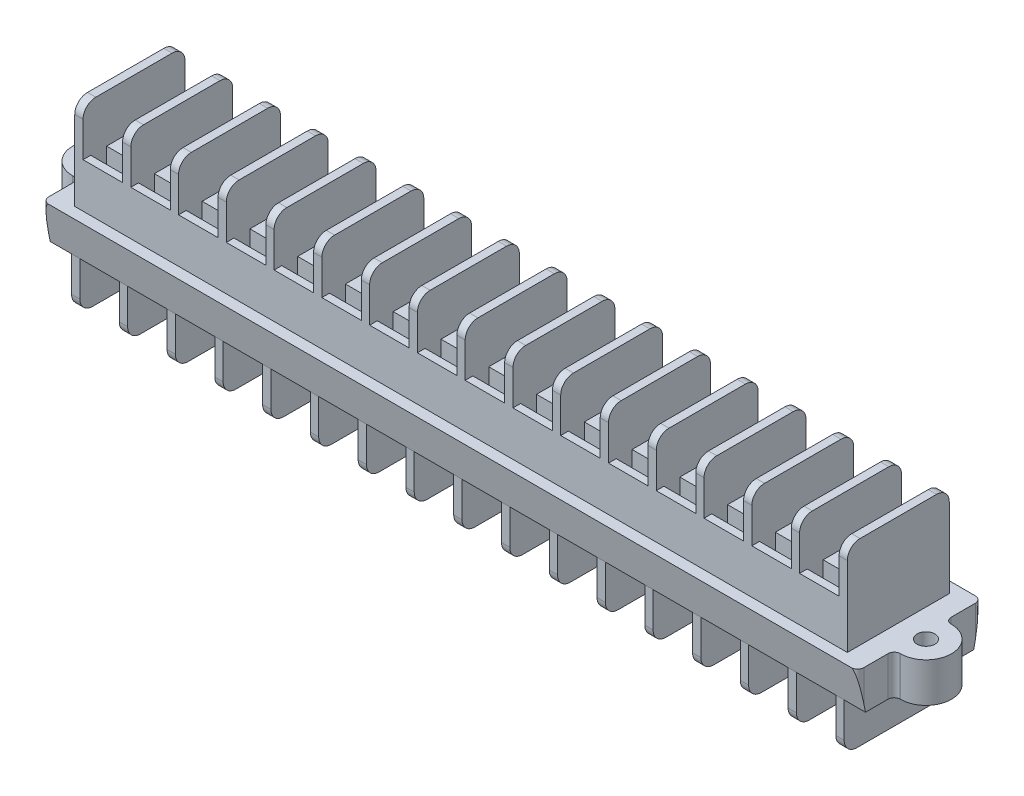
SolidWorks part; units mm, degrees
ref_plane "前视基准面" through (0, 0, 0) normal (0, 0, 1) x (1, 0, 0)
ref_plane "上视基准面" through (0, 0, 0) normal (0, 1, 0) x (1, 0, 0)
ref_plane "右视基准面" through (0, 0, 0) normal (1, 0, 0) x (0, 0, -1)
sketch "草图1" plane through (0, 0, 0) normal (0, 1, 0) x (1, 0, 0)
  line L0 (-82.1935, 0) -> (84.8449, 0) construction
  line L1 (-60.65, 8) -> (60.65, 8)
  line L2 (-60.65, 8) -> (-60.65, -8)
  line L3 (-60.65, -8) -> (60.65, -8)
  line L4 (60.65, 8) -> (60.65, -8)
  line L5 (0, -27.2716) -> (0, 19.3174) construction
  dimension "D1" = 121.3
  dimension "D2" = 16
extrude "拉伸1" add sketch "草图1" along normal blind 14.5
fillet "圆角1" radius 2 2 edges at (0, 14.5, 8) (0, 14.5, -8)
sketch "草图2" plane through (0, 14.5, 0) normal (0, 1, 0) x (-1, 0, 0)
  line L0 (-64.5515, 0) -> (65.0244, 0) construction
  line L1 (-60.65, -8) -> (60.65, -8) construction
  line L2 (-59.35, -8) -> (-53.15, -8)
  line L3 (-59.35, -8) -> (-59.35, 8)
  line L4 (-59.35, 8) -> (-53.15, 8)
  line L5 (-53.15, -8) -> (-53.15, 8)
  line L6 (60.65, 8) -> (-60.65, 8) construction
  line L7 (-60.65, 6) -> (-60.65, -6) construction
  line L8 (-51.85, -8) -> (-45.65, -8)
  line L9 (-51.85, -8) -> (-51.85, 8)
  line L10 (-51.85, 8) -> (-45.65, 8)
  line L11 (-45.65, -8) -> (-45.65, 8)
  line L12 (-44.35, -8) -> (-38.15, -8)
  line L13 (-44.35, -8) -> (-44.35, 8)
  line L14 (-44.35, 8) -> (-38.15, 8)
  line L15 (-38.15, -8) -> (-38.15, 8)
  line L16 (-36.85, -8) -> (-30.65, -8)
  line L17 (-36.85, -8) -> (-36.85, 8)
  line L18 (-36.85, 8) -> (-30.65, 8)
  line L19 (-30.65, -8) -> (-30.65, 8)
  line L20 (-29.35, -8) -> (-23.15, -8)
  line L21 (-29.35, -8) -> (-29.35, 8)
  line L22 (-29.35, 8) -> (-23.15, 8)
  line L23 (-23.15, -8) -> (-23.15, 8)
  line L24 (-21.85, -8) -> (-15.65, -8)
  line L25 (-21.85, -8) -> (-21.85, 8)
  line L26 (-21.85, 8) -> (-15.65, 8)
  line L27 (-15.65, -8) -> (-15.65, 8)
  line L28 (-14.35, -8) -> (-8.15, -8)
  line L29 (-14.35, -8) -> (-14.35, 8)
  line L30 (-14.35, 8) -> (-8.15, 8)
  line L31 (-8.15, -8) -> (-8.15, 8)
  line L32 (-6.85, -8) -> (-0.65, -8)
  line L33 (-6.85, -8) -> (-6.85, 8)
  line L34 (-6.85, 8) -> (-0.65, 8)
  line L35 (-0.65, -8) -> (-0.65, 8)
  line L36 (0.65, -8) -> (6.85, -8)
  line L37 (0.65, -8) -> (0.65, 8)
  line L38 (0.65, 8) -> (6.85, 8)
  line L39 (6.85, -8) -> (6.85, 8)
  line L40 (8.15, -8) -> (14.35, -8)
  line L41 (8.15, -8) -> (8.15, 8)
  line L42 (8.15, 8) -> (14.35, 8)
  line L43 (14.35, -8) -> (14.35, 8)
  line L44 (15.65, -8) -> (21.85, -8)
  line L45 (15.65, -8) -> (15.65, 8)
  line L46 (15.65, 8) -> (21.85, 8)
  line L47 (21.85, -8) -> (21.85, 8)
  line L48 (23.15, -8) -> (29.35, -8)
  line L49 (23.15, -8) -> (23.15, 8)
  line L50 (23.15, 8) -> (29.35, 8)
  line L51 (29.35, -8) -> (29.35, 8)
  line L52 (30.65, -8) -> (36.85, -8)
  line L53 (30.65, -8) -> (30.65, 8)
  line L54 (30.65, 8) -> (36.85, 8)
  line L55 (36.85, -8) -> (36.85, 8)
  line L56 (38.15, -8) -> (44.35, -8)
  line L57 (38.15, -8) -> (38.15, 8)
  line L58 (38.15, 8) -> (44.35, 8)
  line L59 (44.35, -8) -> (44.35, 8)
  line L60 (45.65, -8) -> (51.85, -8)
  line L61 (45.65, -8) -> (45.65, 8)
  line L62 (45.65, 8) -> (51.85, 8)
  line L63 (51.85, -8) -> (51.85, 8)
  line L64 (53.15, -8) -> (59.35, -8)
  line L65 (53.15, -8) -> (53.15, 8)
  line L66 (53.15, 8) -> (59.35, 8)
  line L67 (59.35, -8) -> (59.35, 8)
  dimension "D1" = 1.3
  dimension "D2" = 7.5
extrude "切除-拉伸1" cut sketch "草图2" against normal blind 7.5
sketch "草图3" plane through (0, 0, 0) normal (0, -1, 0) x (1, 0, 0)
  line L0 (63, 9.75) -> (-63, 9.75)
  line L1 (-64, 8.75) -> (-64, 4.95)
  line L2 (-64.95, 4) -> (-65, 4)
  line L3 (76.798, 0) -> (-85.9187, 0) construction
  line L4 (-65, 12.2492) -> (-65, -13.694) construction
  line L5 (-65, -12.2492) -> (-65, 13.694) construction
  line L6 (-64.95, -4) -> (-65, -4)
  line L7 (-64, -8.75) -> (-64, -4.95)
  line L8 (63, -9.75) -> (-63, -9.75)
  line L9 (0, 14.8922) -> (0, -13.694) construction
  line L10 (65, -12.2492) -> (65, 13.694) construction
  line L11 (65, 12.2492) -> (65, -13.694) construction
  line L12 (64, -8.75) -> (64, -4.95)
  line L13 (64.95, -4) -> (65, -4)
  line L14 (64.95, 4) -> (65, 4)
  line L15 (64, 8.75) -> (64, 4.95)
  arc A0 (-65, 4) -> (-65, -4) centre (-65, 0) ccw
  arc A1 (-63, 9.75) -> (-64, 8.75) centre (-63, 8.75) ccw
  arc A2 (-64.95, 4) -> (-64, 4.95) centre (-64.95, 4.95) ccw
  arc A3 (-64.95, -4) -> (-64, -4.95) centre (-64.95, -4.95) cw
  arc A4 (-63, -9.75) -> (-64, -8.75) centre (-63, -8.75) cw
  arc A5 (63, -9.75) -> (64, -8.75) centre (63, -8.75) ccw
  arc A6 (64.95, -4) -> (64, -4.95) centre (64.95, -4.95) ccw
  arc A7 (64.95, 4) -> (64, 4.95) centre (64.95, 4.95) cw
  arc A8 (63, 9.75) -> (64, 8.75) centre (63, 8.75) cw
  arc A9 (65, 4) -> (65, -4) centre (65, 0) cw
  point P8 (0, 9.75)
  point P45 (0, -9.75)
  dimension "D2" = 4
  dimension "D3" = 1
  dimension "D4" = 0.95
  dimension "D6" = 130
  dimension "D1" = 1
  dimension "D5" = 19.5
extrude "拉伸2" add sketch "草图3" along normal blind 6.2
sketch "草图4" plane through (0, -6.2, 0) normal (0, -1, 0) x (1, 0, 0)
  line L0 (72.0936, 0) -> (-72.0936, 0) construction
  line L1 (-60.65, -8) -> (-60.65, 8) construction
  line L2 (-60.65, 8.5) -> (60.65, 8.5)
  line L3 (-60.65, 8.5) -> (-60.65, -8.5)
  line L4 (-60.65, -8.5) -> (60.65, -8.5)
  line L5 (60.65, 8.5) -> (60.65, -8.5)
  line L6 (60.65, 8) -> (60.65, -8) construction
  dimension "D1" = 17
extrude "拉伸3" add sketch "草图4" along normal blind 7.5
sketch "草图5" plane through (-60.65, 0, 0) normal (-1, 0, 0) x (0, 0, 1)
  line L0 (-8.5, -6.2) -> (-9.75, 0)
  line L1 (-9.75, 0) -> (-9.75, -6.2)
  line L2 (-9.75, -6.2) -> (-8.5, -6.2)
  line L3 (8.5, -6.2) -> (9.75, -6.2)
  line L4 (9.75, -6.2) -> (9.75, 0)
  line L5 (9.75, 0) -> (8.5, -6.2)
extrude "切除-拉伸2" cut sketch "草图5" against normal blind 139 and the other way blind 13
sketch "草图7" plane through (0, 0, 0) normal (0, 1, 0) x (-1, 0, 0)
  circle A0 centre (-65, 0) radius 1.4
  circle A1 centre (65, 0) radius 1.4
  dimension "D1" = 2.8
  dimension "D2" = 2.8
extrude "切除-拉伸4" cut sketch "草图7" against normal through all
sketch "草图8" plane through (0, -6.2, 0) normal (0, 1, 0) x (-1, 0, 0)
  circle A0 centre (65, 0) radius 3
  circle A1 centre (-65, 0) radius 3
  dimension "D1" = 6
  dimension "D2" = 6
extrude "切除-拉伸5" cut sketch "草图8" along normal blind 3
fillet "圆角2" radius 2 2 edges at (0, -13.7, 8.5) (0, -13.7, -8.5)
sketch "草图6" plane through (0, -13.7, 0) normal (0, -1, 0) x (1, 0, 0)
  line L0 (60.65, 8.5) -> (-60.65, 8.5) construction
  line L1 (59.35, 8.5) -> (53.15, 8.5)
  line L2 (59.35, 8.5) -> (59.35, -8.5)
  line L3 (59.35, -8.5) -> (53.15, -8.5)
  line L4 (53.15, 8.5) -> (53.15, -8.5)
  line L5 (-60.65, -8.5) -> (60.65, -8.5) construction
  line L6 (60.65, -8.5) -> (60.65, 8.5) construction
  line L7 (51.85, 8.5) -> (45.65, 8.5)
  line L8 (51.85, 8.5) -> (51.85, -8.5)
  line L9 (51.85, -8.5) -> (45.65, -8.5)
  line L10 (45.65, 8.5) -> (45.65, -8.5)
  line L11 (44.35, 8.5) -> (38.15, 8.5)
  line L12 (44.35, 8.5) -> (44.35, -8.5)
  line L13 (44.35, -8.5) -> (38.15, -8.5)
  line L14 (38.15, 8.5) -> (38.15, -8.5)
  line L15 (36.85, 8.5) -> (30.65, 8.5)
  line L16 (36.85, 8.5) -> (36.85, -8.5)
  line L17 (36.85, -8.5) -> (30.65, -8.5)
  line L18 (30.65, 8.5) -> (30.65, -8.5)
  line L19 (29.35, 8.5) -> (23.15, 8.5)
  line L20 (29.35, 8.5) -> (29.35, -8.5)
  line L21 (29.35, -8.5) -> (23.15, -8.5)
  line L22 (23.15, 8.5) -> (23.15, -8.5)
  line L23 (21.85, 8.5) -> (15.65, 8.5)
  line L24 (21.85, 8.5) -> (21.85, -8.5)
  line L25 (21.85, -8.5) -> (15.65, -8.5)
  line L26 (15.65, 8.5) -> (15.65, -8.5)
  line L27 (14.35, 8.5) -> (8.15, 8.5)
  line L28 (14.35, 8.5) -> (14.35, -8.5)
  line L29 (14.35, -8.5) -> (8.15, -8.5)
  line L30 (8.15, 8.5) -> (8.15, -8.5)
  line L31 (6.85, 8.5) -> (0.65, 8.5)
  line L32 (6.85, 8.5) -> (6.85, -8.5)
  line L33 (6.85, -8.5) -> (0.65, -8.5)
  line L34 (0.65, 8.5) -> (0.65, -8.5)
  line L35 (-0.65, 8.5) -> (-6.85, 8.5)
  line L36 (-0.65, 8.5) -> (-0.65, -8.5)
  line L37 (-0.65, -8.5) -> (-6.85, -8.5)
  line L38 (-6.85, 8.5) -> (-6.85, -8.5)
  line L39 (-8.15, 8.5) -> (-14.35, 8.5)
  line L40 (-8.15, 8.5) -> (-8.15, -8.5)
  line L41 (-8.15, -8.5) -> (-14.35, -8.5)
  line L42 (-14.35, 8.5) -> (-14.35, -8.5)
  line L43 (-15.65, 8.5) -> (-21.85, 8.5)
  line L44 (-15.65, 8.5) -> (-15.65, -8.5)
  line L45 (-15.65, -8.5) -> (-21.85, -8.5)
  line L46 (-21.85, 8.5) -> (-21.85, -8.5)
  line L47 (-23.15, 8.5) -> (-29.35, 8.5)
  line L48 (-23.15, 8.5) -> (-23.15, -8.5)
  line L49 (-23.15, -8.5) -> (-29.35, -8.5)
  line L50 (-29.35, 8.5) -> (-29.35, -8.5)
  line L51 (-30.65, 8.5) -> (-36.85, 8.5)
  line L52 (-30.65, 8.5) -> (-30.65, -8.5)
  line L53 (-30.65, -8.5) -> (-36.85, -8.5)
  line L54 (-36.85, 8.5) -> (-36.85, -8.5)
  line L55 (-38.15, 8.5) -> (-44.35, 8.5)
  line L56 (-38.15, 8.5) -> (-38.15, -8.5)
  line L57 (-38.15, -8.5) -> (-44.35, -8.5)
  line L58 (-44.35, 8.5) -> (-44.35, -8.5)
  line L59 (-45.65, 8.5) -> (-51.85, 8.5)
  line L60 (-45.65, 8.5) -> (-45.65, -8.5)
  line L61 (-45.65, -8.5) -> (-51.85, -8.5)
  line L62 (-51.85, 8.5) -> (-51.85, -8.5)
  line L63 (-53.15, 8.5) -> (-59.35, 8.5)
  line L64 (-53.15, 8.5) -> (-53.15, -8.5)
  line L65 (-53.15, -8.5) -> (-59.35, -8.5)
  line L66 (-59.35, 8.5) -> (-59.35, -8.5)
  dimension "D1" = 1.3
  dimension "D2" = 7.5
extrude "切除-拉伸3" cut sketch "草图6" against normal up to surface (7.5 mm away) up to face at (-64.0806, -6.2, 0)
sketch "草图9" plane through (0, 14.5, 0) normal (0, 1, 0) x (-1, 0, 0)
  line L0 (53.15, 8) -> (53.15, -8) construction
  line L1 (77.7153, 0) -> (-90.3068, 0) construction
  line L2 (59.35, -4.3) -> (59.35, -6.8)
  line L3 (53.15, -6.8) -> (59.35, -6.8)
  line L4 (53.15, -4.3) -> (53.15, -6.8)
  line L6 (59.35, 8) -> (59.35, 6) construction
  line L7 (53.15, -4.3) -> (59.35, -4.3)
  line L8 (51.85, -4.3) -> (51.85, -6.8)
  line L9 (45.65, -6.8) -> (51.85, -6.8)
  line L10 (45.65, -4.3) -> (45.65, -6.8)
  line L11 (53.15, 4.3) -> (59.35, 4.3)
  line L12 (53.15, 4.3) -> (53.15, 6.8)
  line L13 (53.15, 6.8) -> (59.35, 6.8)
  line L14 (59.35, 4.3) -> (59.35, 6.8)
  line L16 (60.65, 8) -> (-60.65, 8) construction
  line L17 (45.65, -4.3) -> (51.85, -4.3)
  line L18 (45.65, 4.3) -> (51.85, 4.3)
  line L19 (45.65, 4.3) -> (45.65, 6.8)
  line L20 (45.65, 6.8) -> (51.85, 6.8)
  line L21 (51.85, 4.3) -> (51.85, 6.8)
  line L22 (44.35, -4.3) -> (44.35, -6.8)
  line L23 (38.15, -6.8) -> (44.35, -6.8)
  line L24 (38.15, -4.3) -> (38.15, -6.8)
  line L25 (38.15, -4.3) -> (44.35, -4.3)
  line L26 (38.15, 4.3) -> (44.35, 4.3)
  line L27 (38.15, 4.3) -> (38.15, 6.8)
  line L28 (38.15, 6.8) -> (44.35, 6.8)
  line L29 (44.35, 4.3) -> (44.35, 6.8)
  line L30 (36.85, -4.3) -> (36.85, -6.8)
  line L31 (30.65, -6.8) -> (36.85, -6.8)
  line L32 (30.65, -4.3) -> (30.65, -6.8)
  line L33 (30.65, -4.3) -> (36.85, -4.3)
  line L34 (30.65, 4.3) -> (36.85, 4.3)
  line L35 (30.65, 4.3) -> (30.65, 6.8)
  line L36 (30.65, 6.8) -> (36.85, 6.8)
  line L37 (36.85, 4.3) -> (36.85, 6.8)
  line L38 (29.35, -4.3) -> (29.35, -6.8)
  line L39 (23.15, -6.8) -> (29.35, -6.8)
  line L40 (23.15, -4.3) -> (23.15, -6.8)
  line L41 (23.15, -4.3) -> (29.35, -4.3)
  line L42 (23.15, 4.3) -> (29.35, 4.3)
  line L43 (23.15, 4.3) -> (23.15, 6.8)
  line L44 (23.15, 6.8) -> (29.35, 6.8)
  line L45 (29.35, 4.3) -> (29.35, 6.8)
  line L46 (21.85, -4.3) -> (21.85, -6.8)
  line L47 (15.65, -6.8) -> (21.85, -6.8)
  line L48 (15.65, -4.3) -> (15.65, -6.8)
  line L49 (15.65, -4.3) -> (21.85, -4.3)
  line L50 (15.65, 4.3) -> (21.85, 4.3)
  line L51 (15.65, 4.3) -> (15.65, 6.8)
  line L52 (15.65, 6.8) -> (21.85, 6.8)
  line L53 (21.85, 4.3) -> (21.85, 6.8)
  line L54 (14.35, -4.3) -> (14.35, -6.8)
  line L55 (8.15, -6.8) -> (14.35, -6.8)
  line L56 (8.15, -4.3) -> (8.15, -6.8)
  line L57 (8.15, -4.3) -> (14.35, -4.3)
  line L58 (8.15, 4.3) -> (14.35, 4.3)
  line L59 (8.15, 4.3) -> (8.15, 6.8)
  line L60 (8.15, 6.8) -> (14.35, 6.8)
  line L61 (14.35, 4.3) -> (14.35, 6.8)
  line L62 (6.85, -4.3) -> (6.85, -6.8)
  line L63 (0.65, -6.8) -> (6.85, -6.8)
  line L64 (0.65, -4.3) -> (0.65, -6.8)
  line L65 (0.65, -4.3) -> (6.85, -4.3)
  line L66 (0.65, 4.3) -> (6.85, 4.3)
  line L67 (0.65, 4.3) -> (0.65, 6.8)
  line L68 (0.65, 6.8) -> (6.85, 6.8)
  line L69 (6.85, 4.3) -> (6.85, 6.8)
  line L70 (-0.65, -4.3) -> (-0.65, -6.8)
  line L71 (-6.85, -6.8) -> (-0.65, -6.8)
  line L72 (-6.85, -4.3) -> (-6.85, -6.8)
  line L73 (-6.85, -4.3) -> (-0.65, -4.3)
  line L74 (-6.85, 4.3) -> (-0.65, 4.3)
  line L75 (-6.85, 4.3) -> (-6.85, 6.8)
  line L76 (-6.85, 6.8) -> (-0.65, 6.8)
  line L77 (-0.65, 4.3) -> (-0.65, 6.8)
  line L78 (-8.15, -4.3) -> (-8.15, -6.8)
  line L79 (-14.35, -6.8) -> (-8.15, -6.8)
  line L80 (-14.35, -4.3) -> (-14.35, -6.8)
  line L81 (-14.35, -4.3) -> (-8.15, -4.3)
  line L82 (-14.35, 4.3) -> (-8.15, 4.3)
  line L83 (-14.35, 4.3) -> (-14.35, 6.8)
  line L84 (-14.35, 6.8) -> (-8.15, 6.8)
  line L85 (-8.15, 4.3) -> (-8.15, 6.8)
  line L86 (-15.65, -4.3) -> (-15.65, -6.8)
  line L87 (-21.85, -6.8) -> (-15.65, -6.8)
  line L88 (-21.85, -4.3) -> (-21.85, -6.8)
  line L89 (-21.85, -4.3) -> (-15.65, -4.3)
  line L90 (-21.85, 4.3) -> (-15.65, 4.3)
  line L91 (-21.85, 4.3) -> (-21.85, 6.8)
  line L92 (-21.85, 6.8) -> (-15.65, 6.8)
  line L93 (-15.65, 4.3) -> (-15.65, 6.8)
  line L94 (-23.15, -4.3) -> (-23.15, -6.8)
  line L95 (-29.35, -6.8) -> (-23.15, -6.8)
  line L96 (-29.35, -4.3) -> (-29.35, -6.8)
  line L97 (-29.35, -4.3) -> (-23.15, -4.3)
  line L98 (-29.35, 4.3) -> (-23.15, 4.3)
  line L99 (-29.35, 4.3) -> (-29.35, 6.8)
  line L100 (-29.35, 6.8) -> (-23.15, 6.8)
  line L101 (-23.15, 4.3) -> (-23.15, 6.8)
  line L102 (-30.65, -4.3) -> (-30.65, -6.8)
  line L103 (-36.85, -6.8) -> (-30.65, -6.8)
  line L104 (-36.85, -4.3) -> (-36.85, -6.8)
  line L105 (-36.85, -4.3) -> (-30.65, -4.3)
  line L106 (-36.85, 4.3) -> (-30.65, 4.3)
  line L107 (-36.85, 4.3) -> (-36.85, 6.8)
  line L108 (-36.85, 6.8) -> (-30.65, 6.8)
  line L109 (-30.65, 4.3) -> (-30.65, 6.8)
  line L110 (-38.15, -4.3) -> (-38.15, -6.8)
  line L111 (-44.35, -6.8) -> (-38.15, -6.8)
  line L112 (-44.35, -4.3) -> (-44.35, -6.8)
  line L113 (-44.35, -4.3) -> (-38.15, -4.3)
  line L114 (-44.35, 4.3) -> (-38.15, 4.3)
  line L115 (-44.35, 4.3) -> (-44.35, 6.8)
  line L116 (-44.35, 6.8) -> (-38.15, 6.8)
  line L117 (-38.15, 4.3) -> (-38.15, 6.8)
  line L118 (-45.65, -4.3) -> (-45.65, -6.8)
  line L119 (-51.85, -6.8) -> (-45.65, -6.8)
  line L120 (-51.85, -4.3) -> (-51.85, -6.8)
  line L121 (-51.85, -4.3) -> (-45.65, -4.3)
  line L122 (-51.85, 4.3) -> (-45.65, 4.3)
  line L123 (-51.85, 4.3) -> (-51.85, 6.8)
  line L124 (-51.85, 6.8) -> (-45.65, 6.8)
  line L125 (-45.65, 4.3) -> (-45.65, 6.8)
  line L126 (-53.15, -4.3) -> (-53.15, -6.8)
  line L127 (-59.35, -6.8) -> (-53.15, -6.8)
  line L128 (-59.35, -4.3) -> (-59.35, -6.8)
  line L129 (-59.35, -4.3) -> (-53.15, -4.3)
  line L130 (-59.35, 4.3) -> (-53.15, 4.3)
  line L131 (-59.35, 4.3) -> (-59.35, 6.8)
  line L132 (-59.35, 6.8) -> (-53.15, 6.8)
  line L133 (-53.15, 4.3) -> (-53.15, 6.8)
  dimension "D2" = 2.5
  dimension "D3" = 1.2
extrude "切除-拉伸6" cut sketch "草图9" against normal offset from surface (19.2 mm away) 1.5 up to face at (-48.75, -6.2, 0)
